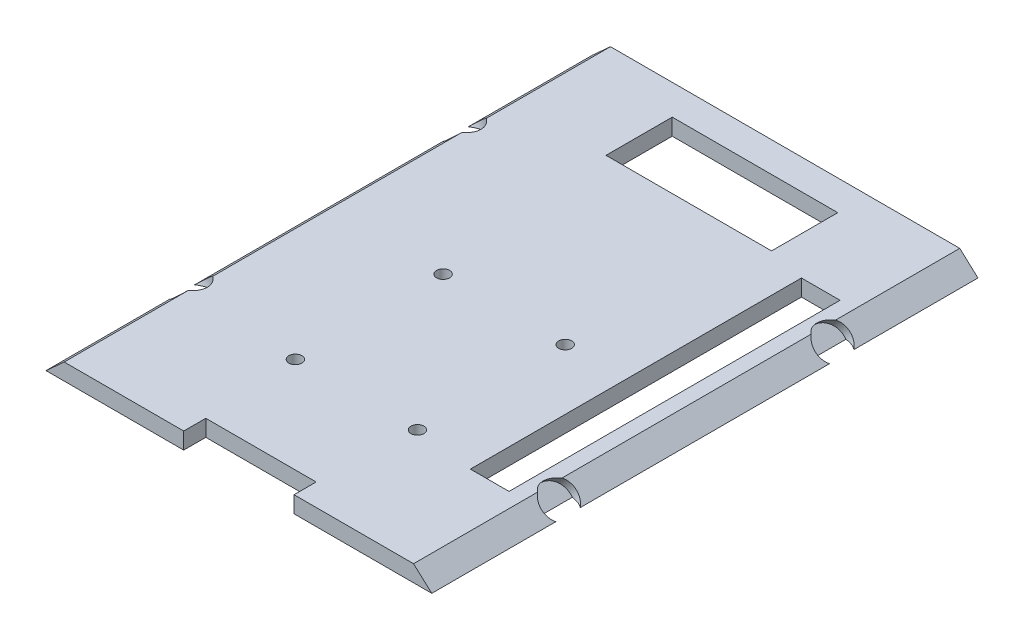
SolidWorks part; units mm, degrees
ref_plane "Front Plane" through (0, 0, 0) normal (0, 0, 1) x (1, 0, 0)
ref_plane "Top Plane" through (0, 0, 0) normal (0, 1, 0) x (1, 0, 0)
ref_plane "Right Plane" through (0, 0, 0) normal (1, 0, 0) x (0, 0, -1)
sketch "Sketch1" plane through (0, 0, 0) normal (0, 0, 1) x (1, 0, 0)
  line L0 (0, 0) -> (0, 44.45) construction
  line L1 (-40.2039, 5.9378) -> (40.2039, 5.9378)
  line L2 (-44.399, 2.1278) -> (44.399, 2.1278)
  line L3 (-40.2039, 5.9378) -> (-44.399, 2.1278)
  line L4 (40.2039, 5.9378) -> (44.399, 2.1278)
  arc A0 (44.399, 2.1278) -> (-44.399, 2.1278) centre (0, 0) ccw construction
  arc A1 (40.2039, 5.9378) -> (-40.2039, 5.9378) centre (0, 0) ccw construction
  dimension "D1" = 88.9
  dimension "D2" = 3.81
  dimension "D3" = 3.81
extrude "Boss-Extrude1" add sketch "Sketch1" along normal blind 125.73
sketch "Sketch3" plane through (0, 2.1278, 0) normal (0, -1, 0) x (1, 0, 0)
  line L0 (0, 125.73) -> (0, 0) construction
  line L1 (-44.399, 125.73) -> (44.399, 125.73) construction
  line L2 (-44.399, 0) -> (44.399, 0) construction
  line L3 (0, 62.865) -> (44.399, 62.865) construction
  line L4 (-12.7, 125.73) -> (12.7, 125.73)
  line L5 (-12.7, 125.73) -> (-12.7, 120.65)
  line L6 (-12.7, 120.65) -> (12.7, 120.65)
  line L7 (12.7, 125.73) -> (12.7, 120.65)
  line L8 (44.399, 125.73) -> (44.399, 0) construction
  line L9 (0, 62.865) -> (-44.399, 62.865) construction
  line L10 (-44.399, 125.73) -> (-44.399, 0) construction
  line L11 (12.7, -5.08) -> (12.7, 0) construction
  line L13 (-12.7, 0) -> (12.7, 0) construction
  line L14 (-12.7, -5.08) -> (-12.7, 0) construction
  line L15 (-12.7, -5.08) -> (12.7, -5.08) construction
  point P10 (12.7, 123.19)
  dimension "D1" = 25.4
  dimension "D2" = 12.7
  dimension "D3" = 5.08
extrude "Cut-Extrude1" cut sketch "Sketch3" against normal through all
sketch "Sketch5" plane through (0, 2.1278, 0) normal (0, -1, 0) x (1, 0, 0)
  line L0 (12.7, 125.73) -> (44.399, 125.73) construction
  line L1 (27.889, 100.33) -> (36.779, 100.33)
  line L2 (27.889, 100.33) -> (27.889, 24.13)
  line L3 (27.889, 24.13) -> (36.779, 24.13)
  line L4 (36.779, 100.33) -> (36.779, 24.13)
  line L5 (44.399, 125.73) -> (44.399, 0) construction
  dimension "D1" = 76.2
  dimension "D2" = 25.4
  dimension "D3" = 7.62
  dimension "D4" = 8.89
extrude "Cut-Extrude3" cut sketch "Sketch5" against normal through all
sketch "Sketch6" plane through (0, 2.1278, 0) normal (0, -1, 0) x (1, 0, 0)
  line L0 (0, 22.173) -> (0, 6.933) construction
  line L1 (-19.05, 22.173) -> (19.05, 22.173)
  line L2 (-19.05, 22.173) -> (-19.05, 6.933)
  line L3 (-19.05, 6.933) -> (19.05, 6.933)
  line L4 (19.05, 22.173) -> (19.05, 6.933)
  line L5 (0, 120.65) -> (0, 0) construction
  line L6 (-12.7, 120.65) -> (12.7, 120.65) construction
  line L7 (-44.399, 0) -> (44.399, 0) construction
  dimension "D1" = 38.1
  dimension "D2" = 15.24
  dimension "D3" = 0
extrude "Cut-Extrude4" cut sketch "Sketch6" against normal through all
sketch "Sketch7" plane through (21.1272, 23.263, 0) normal (0.6723, 0.7403, 0) x (0.7403, -0.6723, 0)
  line L0 (28.6033, -125.73) -> (28.6033, 0) construction
  line L1 (31.4368, -125.73) -> (25.7698, -125.73) construction
  line L2 (25.7698, -62.865) -> (31.4368, -62.865) construction
  line L3 (25.7698, -125.73) -> (25.7698, 0) construction
  line L4 (31.4368, -125.73) -> (31.4368, 0) construction
  circle A0 centre (28.6033, -94.361) radius 4.0005
  circle A1 centre (28.6033, -31.369) radius 4.0005
  point P6 (28.6033, -62.865)
  dimension "D1" = 8.001
  dimension "D2" = 31.496
  dimension "D3" = 125.73
extrude "Cut-Extrude5" cut sketch "Sketch7" against normal blind 2
sketch "Sketch8" plane through (-21.1272, 23.263, 0) normal (-0.6723, 0.7403, 0) x (0.7403, 0.6723, 0)
  line L0 (-28.6033, 0) -> (-28.6033, -125.73) construction
  line L1 (-25.7698, 0) -> (-31.4368, 0) construction
  line L2 (-25.7698, -62.865) -> (-31.4368, -62.865) construction
  line L3 (-25.7698, -125.73) -> (-25.7698, 0) construction
  line L4 (-31.4368, -125.73) -> (-31.4368, 0) construction
  circle A0 centre (-28.6033, -31.369) radius 4.0005
  circle A1 centre (-28.6033, -94.361) radius 4.0005
  point P12 (-28.6033, -62.865)
  dimension "D1" = 8.001
  dimension "D2" = 31.496
  dimension "D3" = 125.73
extrude "Cut-Extrude6" cut sketch "Sketch8" against normal blind 2
sketch "Sketch9" plane through (0, 5.9378, 0) normal (0, 1, 0) x (1, 0, 0)
  line L0 (-0.0719, -125.73) -> (-0.0719, 0) construction
  line L1 (-0.0719, -103.6016) -> (-0.0719, -59.6016) construction
  line L2 (18.9781, -103.6016) -> (-19.1219, -103.6016) construction
  line L3 (40.2039, 0) -> (-40.2039, 0) construction
  line L4 (18.9781, -103.6016) -> (18.9781, -59.6016) construction
  line L5 (40.2039, -62.865) -> (-40.2039, -62.865) construction
  line L6 (18.9781, -59.6016) -> (-19.1219, -59.6016) construction
  line L7 (40.2039, -91.537) -> (40.2039, -34.193) construction
  line L8 (-40.2039, -91.537) -> (-40.2039, -34.193) construction
  line L9 (-19.1219, -103.6016) -> (-19.1219, -59.6016) construction
  line L11 (-40.2039, -125.73) -> (-40.2039, -97.185) construction
  line L12 (18.9781, -81.6016) -> (-19.1219, -81.6016) construction
  circle A0 centre (13.9781, -98.6016) radius 1.5
  circle A1 centre (-14.1219, -98.6016) radius 1.5
  circle A2 centre (-14.1219, -64.6016) radius 1.5
  circle A3 centre (13.9781, -64.6016) radius 1.5
  dimension "D8" = 3
  dimension "D1" = 125.73
  dimension "D2" = 44
  dimension "D3" = 38.1
  dimension "D4" = 0
  dimension "D5" = 40.132
  dimension "D6" = 5
  dimension "D7" = 5
extrude "Cut-Extrude8" cut sketch "Sketch9" against normal through all
